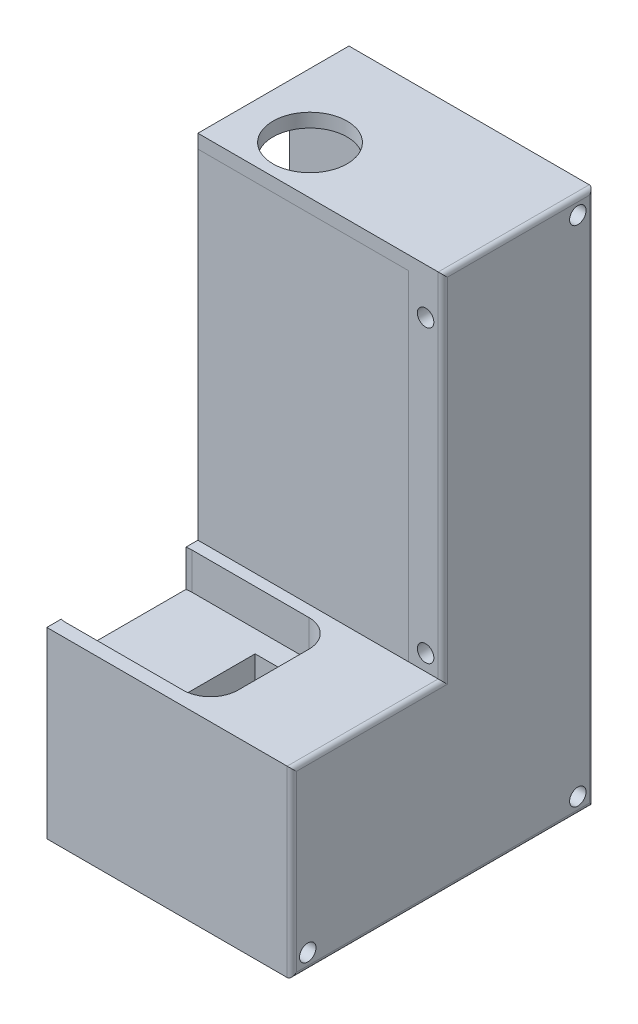
SolidWorks part; units mm, degrees
material "ABS"
ref_plane "Front" through (0, 0, 0) normal (0, 0, 1) x (1, 0, 0)
ref_plane "Top" through (0, 0, 0) normal (0, 1, 0) x (1, 0, 0)
ref_plane "Right" through (0, 0, 0) normal (1, 0, 0) x (0, 0, -1)
sketch "ｽｹｯﾁ1" plane through (0, 0, 0) normal (1, 0, 0) x (0, 0, -1)
  line L0 (23, 92) -> (0, 92)
  line L1 (33, 92) -> (23, 92)
  line L2 (33, 92) -> (33, -25)
  line L3 (33, -25) -> (23, -25)
  line L4 (23, 92) -> (23, -25)
  line L5 (0, 92) -> (0, -25)
  line L6 (0, -25) -> (23, -25)
  line L7 (0, -25) -> (-33, -25)
  line L8 (-33, -25) -> (-33, 0)
  line L9 (-33, 0) -> (0, 0)
  dimension "D1" = 117
  dimension "D2" = 10
  dimension "D3" = 33
  dimension "D4" = 23
  dimension "D5" = 25
extrude "ﾎﾞｽ - 押し出し1" add sketch "ｽｹｯﾁ1" along normal blind 77 contours L9 L8 L7 L5 | L5 L6 L4 L0 | L1 L4 L3 L2
sketch "ｽｹｯﾁ2" plane through (0, 0, -33) normal (0, 0, -1) x (-1, 0, 0)
  line L1 (-7.5, 22.5) -> (-69.5, 22.5)
  line L2 (-7.5, 22.5) -> (-7.5, 84.5)
  line L3 (-7.5, 84.5) -> (-69.5, 84.5)
  line L4 (-69.5, 22.5) -> (-69.5, 84.5)
  line L5 (-7.5, 22.5) -> (-69.5, 84.5) construction
  line L6 (-7.5, 84.5) -> (-69.5, 22.5) construction
  line L8 (0, 92) -> (0, -25) construction
  line L9 (-77, 92) -> (0, 92) construction
  point P0 (-38.5, 53.5)
  dimension "D1" = 62
  dimension "D2" = 62
  dimension "D3" = 7.5
  dimension "D4" = 7.5
extrude "ｶｯﾄ - 押し出し1" cut sketch "ｽｹｯﾁ2" against normal blind 10
sketch "ｽｹｯﾁ3" plane through (0, 92, 0) normal (0, 1, 0) x (1, 0, 0)
  line L1 (0, 33) -> (0, 0) construction
  line L2 (77, 0) -> (0, 0) construction
  circle A0 centre (37.5, 10.5) radius 8.1
  dimension "D1" = 16.2
  dimension "D2" = 37.5
  dimension "D3" = 10.5
extrude "ｶｯﾄ - 押し出し2" cut sketch "ｽｹｯﾁ3" against normal blind 10
sketch "ｽｹｯﾁ4" plane through (0, 0, -33) normal (0, 0, -1) x (-1, 0, 0)
  line L0 (-77, -25) -> (0, -25) construction
  line L1 (-7.5, 22.5) -> (-69.5, 22.5)
  line L2 (-7.5, 22.5) -> (-7.5, -17.5)
  line L3 (-7.5, -17.5) -> (-69.5, -17.5)
  line L4 (-69.5, 22.5) -> (-69.5, -17.5)
  dimension "D1" = 7.5
extrude "ｶｯﾄ - 押し出し3" cut sketch "ｽｹｯﾁ4" against normal offset from surface (58.5 mm away) 7.5 up to face at (38.5, -12.5, 33)
sketch "ｽｹｯﾁ5" plane through (0, 0, 0) normal (0, 1, 0) x (1, 0, 0)
  line L1 (50.25, -2.5) -> (24.75, -2.5)
  line L2 (56.25, -8.5) -> (56.25, -24)
  line L3 (50.25, -30) -> (24.75, -30)
  line L4 (18.75, -8.5) -> (18.75, -24)
  line L5 (56.25, -2.5) -> (18.75, -30) construction
  line L6 (56.25, -30) -> (18.75, -2.5) construction
  line L7 (0, -33) -> (0, 0) construction
  line L11 (77, -33) -> (0, -33)
  line L12 (77, -33) -> (77, 0)
  line L13 (77, 0) -> (0, 0)
  line L14 (0, -33) -> (0, 0)
  arc A0 (18.75, -8.5) -> (24.75, -2.5) centre (24.75, -8.5) cw
  arc A1 (56.25, -8.5) -> (50.25, -2.5) centre (50.25, -8.5) ccw
  arc A2 (56.25, -24) -> (50.25, -30) centre (50.25, -24) cw
  arc A3 (24.75, -30) -> (18.75, -24) centre (24.75, -24) cw
  point P0 (37.5, -16.25)
  dimension "D5" = 6
  dimension "D1" = 27.5
  dimension "D2" = 37.5
  dimension "D3" = 37.5
  dimension "D4" = 3
extrude "ﾎﾞｽ - 押し出し2" add sketch "ｽｹｯﾁ5" along normal blind 15
sketch "ｽｹｯﾁ6" plane through (0, 0, 0) normal (0, 1, 0) x (1, 0, 0)
  line L20 (43.25, -30) -> (43.25, -2.5)
  line L21 (51.25, -30) -> (51.25, -2.5839)
  line L22 (43.25, -25.25) -> (51.25, -25.25)
  line L24 (50.25, -2.5) -> (24.75, -2.5)
  line L25 (56.25, -24) -> (56.25, -8.5)
  line L26 (24.75, -30) -> (50.25, -30)
  line L27 (18.75, -8.5) -> (18.75, -24)
  line L28 (50.25, -2.5) -> (24.75, -2.5)
  line L29 (56.25, -24) -> (56.25, -8.5)
  line L30 (24.75, -30) -> (50.25, -30)
  line L31 (18.75, -8.5) -> (18.75, -24)
  line L32 (43.25, -7.25) -> (51.25, -7.25)
  arc A21 (24.75, -2.5) -> (18.75, -8.5) centre (24.75, -8.5) ccw
  arc A22 (56.25, -8.5) -> (50.25, -2.5) centre (50.25, -8.5) ccw
  arc A23 (50.25, -30) -> (56.25, -24) centre (50.25, -24) ccw
  arc A24 (18.75, -24) -> (24.75, -30) centre (24.75, -24) ccw
  arc A25 (24.75, -2.5) -> (18.75, -8.5) centre (24.75, -8.5) ccw
  arc A26 (56.25, -8.5) -> (50.25, -2.5) centre (50.25, -8.5) ccw
  arc A27 (50.25, -30) -> (56.25, -24) centre (50.25, -24) ccw
  arc A28 (18.75, -24) -> (24.75, -30) centre (24.75, -24) ccw
  arc M14 (18.9405, -25.5) -> (24.75, -30) centre (24.75, -24) ccw
  line M15 (24.75, -30) -> (50.25, -30)
  arc M16 (50.25, -30) -> (56.0595, -25.5) centre (50.25, -24) ccw
  line M17 (56.0595, -25.5) -> (18.9405, -25.5)
  dimension "D2" = 13
  dimension "D3" = 8
  dimension "D4" = 18
  dimension "D5" = 4.75
  dimension "D1" = 0
extrude "ﾎﾞｽ - 押し出し3" add sketch "ｽｹｯﾁ6" along normal blind 7 contours L31 A28 L20 L28 A25 M17 | L20 M15 M17 M14 | L21 L20 M16 M17 M15 | A27 L29 A26 L21 M17 | L21 M16 M17 | L21 A26 L28 L20 L32
sketch "ｽｹｯﾁ7" plane through (0, 0, 0) normal (0, 0, 1) x (1, 0, 0)
  line L0 (0, 92) -> (0, 15) construction
  line L1 (69.5, 89) -> (7.5, 89)
  line L2 (69.5, 89) -> (69.5, 22.5)
  line L3 (69.5, 22.5) -> (7.5, 22.5)
  line L4 (7.5, 89) -> (7.5, 22.5)
  line L5 (69.5, 89) -> (7.5, 22.5) construction
  line L6 (69.5, 22.5) -> (7.5, 89) construction
  line L7 (77, 92) -> (0, 92) construction
  line L9 (69.5, 22.5) -> (7.5, 22.5) construction
  line L10 (69.5, 84.5) -> (69.5, -17.5) construction
  point P0 (38.5, 55.75)
  dimension "D1" = 7.5
  dimension "D2" = 3
extrude "ｶｯﾄ - 押し出し4" cut sketch "ｽｹｯﾁ7" against normal offset from surface (20 mm away) 3 up to face at (38.5, 53.5, -23)
sketch "ｽｹｯﾁ8" plane through (0, 89, 0) normal (0, -1, 0) x (-1, 0, 0)
  line L0 (-69.5, 20) -> (-69.5, 0) construction
  line L1 (-7.5, 0) -> (-69.5, 0)
  line L2 (-7.5, 0) -> (-7.5, 2)
  line L3 (-7.5, 2) -> (-69.5, 2)
  line L4 (-69.5, 0) -> (-69.5, 2)
  dimension "D1" = 2
extrude "ﾎﾞｽ - 押し出し4" add sketch "ｽｹｯﾁ8" along normal up to vertex (89 mm away) separate body
sketch "ｽｹｯﾁ9" plane through (0, 0, 0) normal (-1, 0, 0) x (0, 0, 1)
  line L0 (-33, 92) -> (0, 92) construction
  line L1 (-33, 92) -> (-33, -25) construction
  line L2 (-33, -25) -> (33, -25) construction
  line L3 (33, -25) -> (33, 15) construction
  circle A0 centre (-29.5, 88.5) radius 1.8
  circle A1 centre (-29.5, -21.5) radius 1.8
  circle A2 centre (29.5, -21.5) radius 1.8
  dimension "D3" = 3.6
  dimension "D5" = 3.5
  dimension "D1" = 3.5
  dimension "D2" = 3.5
  dimension "D4" = 3.5
extrude "ｶｯﾄ - 押し出し5" cut sketch "ｽｹｯﾁ9" against normal through all
sketch "ｽｹｯﾁ10" plane through (0, 0, 0) normal (0, 0, 1) x (1, 0, 0)
  line L0 (77, 92) -> (0, 92) construction
  line L1 (7.5, 15) -> (0, 15) construction
  line L2 (0, 92) -> (0, 15) construction
  line L3 (77, 92) -> (77, 15) construction
  circle A0 centre (3.75, 82) radius 1.8
  circle A1 centre (73.25, 82) radius 1.8
  circle A2 centre (73.25, 18.5) radius 1.8
  circle A3 centre (3.75, 18.5) radius 1.8
  dimension "D3" = 3.6
  dimension "D1" = 3.5
  dimension "D2" = 10
  dimension "D4" = 3.75
  dimension "D5" = 3.75
extrude "ｶｯﾄ - 押し出し6" cut sketch "ｽｹｯﾁ10" against normal through all
sketch "ｽｹｯﾁ12" plane through (0, 0, -23) normal (0, 0, -1) x (-1, 0, 0)
  line L0 (-69.5, 84.5) -> (-69.5, 22.5) construction
  line L1 (-7.5, 84.5) -> (-69.5, 84.5) construction
  circle A0 centre (-66.5, 81.5) radius 1.8
  circle A1 centre (-11.5, 81.5) radius 1.8
  circle A2 centre (-11.5, 26.5) radius 1.8
  circle A3 centre (-66.5, 26.5) radius 1.8
  dimension "D3" = 3.6
  dimension "D1" = 55
  dimension "D2" = 55
  dimension "D4" = 3
  dimension "D5" = 3
extrude "ｶｯﾄ - 押し出し7" cut sketch "ｽｹｯﾁ12" against normal up to next (3 mm away)
sketch "ｽｹｯﾁ13" plane through (0, 0, -33) normal (0, 0, -1) x (-1, 0, 0)
  line L0 (0, 92) -> (0, -25) construction
  line L1 (0, 30.5) -> (-7.5, 30.5)
  line L2 (0, 30.5) -> (0, 42)
  line L3 (0, 42) -> (-7.5, 42)
  line L4 (-7.5, 30.5) -> (-7.5, 42)
  line L5 (-7.5, -17.5) -> (-7.5, 84.5) construction
  line L6 (-69.5, 22.5) -> (-7.5, 22.5) construction
  point P10 (-3.75, 42)
  dimension "D1" = 8
  dimension "D2" = 19.5
extrude "ｶｯﾄ - 押し出し8" cut sketch "ｽｹｯﾁ13" against normal blind 10
sketch "ｽｹｯﾁ14" plane through (0, 0, -23) normal (0, 0, -1) x (-1, 0, 0)
  line L0 (-69.5, 78) -> (-63, 78)
  line L1 (-69.5, 84.5) -> (-69.5, 22.5) construction
  line L2 (-63, 78) -> (-63, 84.5)
  line L3 (-7.5, 84.5) -> (-69.5, 84.5) construction
  line L4 (-15.5, 84.5) -> (-15.5, 78)
  line L5 (-15.5, 78) -> (-7.5, 78)
  line L6 (-7.5, 42) -> (-7.5, 84.5) construction
  line L8 (-69.5, 22.5) -> (-7.5, 22.5) construction
  line L10 (-7.5, 30.5) -> (-15.5, 30.5)
  line L11 (-15.5, 30.5) -> (-15.5, 22.5)
  line L12 (-15.5, 22.5) -> (-7.5, 22.5)
  line L13 (-7.5, 22.5) -> (-7.5, 30.5)
  line L14 (-69.5, 30.5) -> (-69.5, 22.5)
  line L16 (-63, 84.5) -> (-69.5, 84.5)
  line L17 (-69.5, 84.5) -> (-69.5, 78)
  line L18 (-15.5, 84.5) -> (-7.5, 84.5)
  line L19 (-7.5, 84.5) -> (-7.5, 78)
  line L20 (-69.5, 30.5) -> (-63, 30.5)
  line L21 (-63, 30.5) -> (-63, 22.5)
  line L22 (-63, 22.5) -> (-69.5, 22.5)
  circle A7 centre (-11.5, 81.5) radius 1.8
  circle A8 centre (-11.5, 81.5) radius 1.8
  circle A10 centre (-11.5, 26.5) radius 1.8
  circle A11 centre (-11.5, 26.5) radius 1.8
  circle A13 centre (-66.5, 81.5) radius 1.8
  circle A14 centre (-66.5, 81.5) radius 1.8
  circle A16 centre (-66.5, 26.5) radius 1.8
  circle A17 centre (-66.5, 26.5) radius 1.8
  dimension "D1" = 6.5
  dimension "D2" = 6.5
  dimension "D3" = 0
  dimension "D4" = 0
  dimension "D5" = 0
  dimension "D6" = 0
extrude "ﾎﾞｽ - 押し出し6" add sketch "ｽｹｯﾁ14" along normal blind 2
sketch "ｽｹｯﾁ15" plane through (0, 0, 0) normal (-1, 0, 0) x (0, 0, 1)
  line L20 (-23, 42) -> (-23, 30.5)
  line L21 (-23, 30.5) -> (-33, 30.5)
  line L22 (-33, 30.5) -> (-33, -25)
  line L23 (-33, -25) -> (33, -25)
  line L24 (33, -25) -> (33, 15)
  line L25 (33, 15) -> (0, 15)
  line L26 (0, 15) -> (0, 92)
  line L27 (0, 92) -> (-33, 92)
  line L28 (-33, 92) -> (-33, 42)
  line L29 (-33, 42) -> (-23, 42)
  line L30 (-23, 42) -> (-23, 30.5)
  line L31 (-23, 30.5) -> (-33, 30.5)
  line L32 (-33, 30.5) -> (-33, -25)
  line L33 (-33, -25) -> (33, -25)
  line L34 (33, -25) -> (33, 15)
  line L35 (33, 15) -> (0, 15)
  line L36 (0, 15) -> (0, 92)
  line L37 (0, 92) -> (-33, 92)
  line L38 (-33, 92) -> (-33, 42)
  line L39 (-33, 42) -> (-23, 42)
  dimension "D1" = 0
extrude "ｶｯﾄ - 押し出し9" cut sketch "ｽｹｯﾁ15" against normal blind 23.5
sketch "ｽｹｯﾁ17" plane through (0, -17.5, 0) normal (0, 1, 0) x (1, 0, 0)
  line L0 (23.5, 33) -> (23.5, -25.5) construction
  line L1 (69.5, -25.5) -> (23.5, -25.5)
  line L2 (69.5, -25.5) -> (69.5, 25.5)
  line L3 (69.5, 25.5) -> (23.5, 25.5)
  line L4 (23.5, -25.5) -> (23.5, 25.5)
  line L5 (69.5, 33) -> (23.5, 33) construction
  dimension "D1" = 7.5
extrude "ｶｯﾄ - 押し出し11" cut sketch "ｽｹｯﾁ17" against normal offset from surface (4.5 mm away) 3 up to face at (50.25, -25, 0)
sketch "ｽｹｯﾁ18" plane through (0, 0, 25.5) normal (0, 0, -1) x (-1, 0, 0)
  line L0 (-23.5, -22) -> (-23.5, 0) construction
  line L1 (-69.5, 0) -> (-23.5, 0)
  line L2 (-69.5, 0) -> (-69.5, -17.5)
  line L3 (-69.5, -17.5) -> (-23.5, -17.5)
  line L4 (-23.5, 0) -> (-23.5, -17.5)
  line L5 (-77, -25) -> (-23.5, -25) construction
  dimension "D1" = 7.5
extrude "ｶｯﾄ - 押し出し12" cut sketch "ｽｹｯﾁ18" against normal offset from surface (4.5 mm away) 3 up to face at (50.25, -5, 33)
fillet "ﾌｨﾚｯﾄ1" radius 1 6 edges at (77, 15, 16.5) (77, -5, 33) (77, -25, 0) (77, 33.5, -33) (77, 92, -16.5) (77, 53.5, 0)
